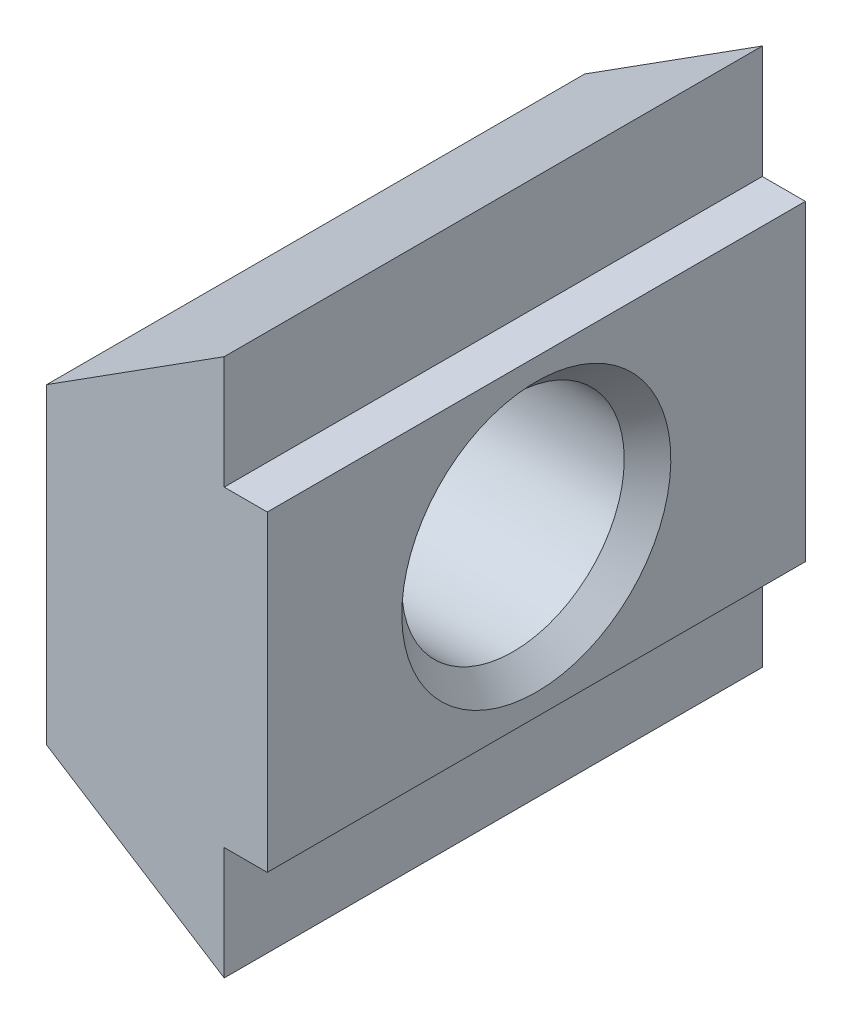
SolidWorks part; units mm, degrees
ref_plane "Front Plane" through (0, 0, 0) normal (0, 0, 1) x (1, 0, 0)
ref_plane "Top Plane" through (0, 0, 0) normal (0, 1, 0) x (1, 0, 0)
ref_plane "Right Plane" through (0, 0, 0) normal (1, 0, 0) x (0, 0, -1)
ref_plane "Plane1" through (0, 0, 5) normal (0, 0, 1) x (1, 0, 0)
sketch "Sketch1" plane through (0, 0, 5) normal (0, 0, 1) x (1, 0, 0)
  line L0 (-0.8, -5) -> (-0.8, 5)
  line L1 (-0.8, 5) -> (-4.1, 2.9)
  line L2 (-4.1, 2.9) -> (-4.1, -2.9)
  line L3 (-4.1, -2.9) -> (-0.8, -5)
extrude "Boss-Extrude1" add sketch "Sketch1" against normal blind 10
sketch "Sketch2" plane through (-0.8, 0, 0) normal (1, 0, 0) x (0, 0, -1)
  line L0 (5, 2.9) -> (5, -2.9)
  line L1 (5, -2.9) -> (-5, -2.9)
  line L2 (-5, -2.9) -> (-5, 2.9)
  line L3 (-5, 2.9) -> (5, 2.9)
extrude "Boss-Extrude2" add sketch "Sketch2" along normal blind 0.8
hole_wizard "M3.5 Clearance Hole1" positions "Sketch4" profile "Sketch3" hole size "M3.5" standard "ANSI Metric"
sketch "Sketch4" plane through (-4.1, 0, 0) normal (-1, 0, 0) x (0, 0, 1)
  point P0 (0, 0)
sketch "Sketch3" plane through (-4.1, 0, 0) normal (0, 1, 0) x (0, 0, 1)
  line L0 (0, 0) -> (0, 4.1)
  line L1 (0, 4.1) -> (2.067, 4.1)
  line L2 (2.067, 4.1) -> (2.067, 0)
  line L5 (2.067, 0) -> (0, 0)
  line L11 (0, -6.35) -> (0, 107.95) construction
  dimension "Thru Hole Dia." = 4.134
  dimension "Thru Hole Depth" = 4.1
chamfer "Chamfer1" distance 0.433 angle 45 2 edges at (0, 0, 2.067) (-4.1, 0, 2.067)
